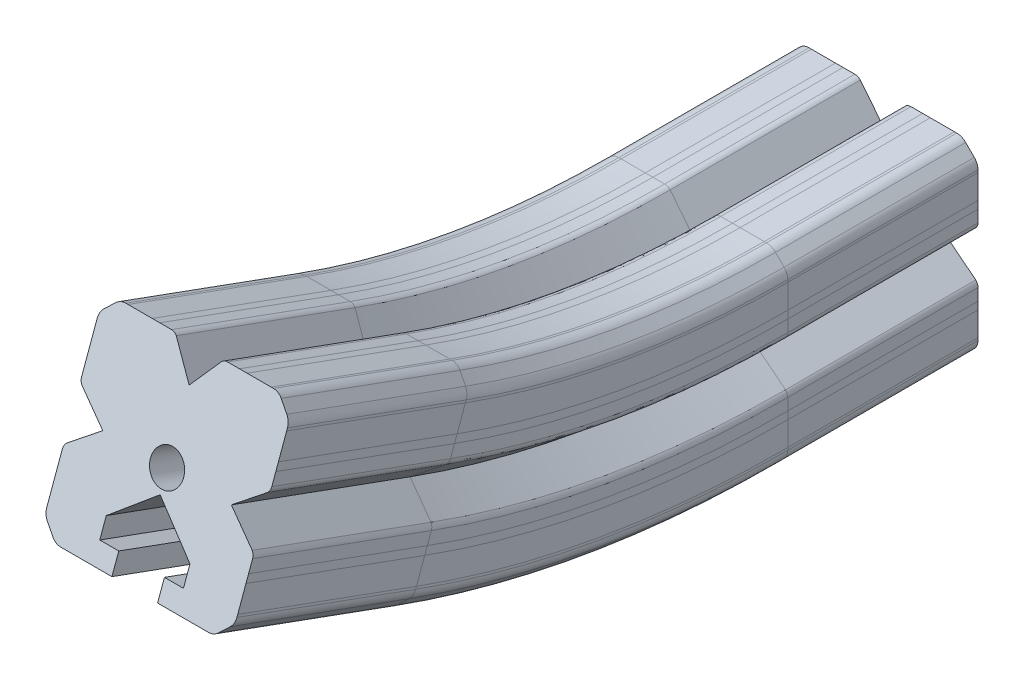
SolidWorks part; units mm, degrees
material "PET"
ref_plane "Front Plane" through (0, 0, 0) normal (0, 0, 1) x (1, 0, 0)
ref_plane "Top Plane" through (0, 0, 0) normal (0, 1, 0) x (1, 0, 0)
ref_plane "Right Plane" through (0, 0, 0) normal (1, 0, 0) x (0, 0, -1)
ref_plane "Plane1" through (0, 0, -304.8) normal (0, 0, -1) x (-1, 0, 0)
sketch "Sketch1" plane through (0, 0, -304.8) normal (0, 0, -1) x (-1, 0, 0)
  line L0 (14.3277, 19.117) -> (9.4982, 19.117)
  line L1 (7.9742, 19.117) -> (5.6176, 19.117)
  line L2 (4.064, 17.5634) -> (4.064, 16.6067) construction
  line L10 (-4.064, 16.6067) -> (-4.064, 17.5634) construction
  line L11 (-5.6176, 19.117) -> (-7.9742, 19.117)
  line L12 (-9.4982, 19.117) -> (-14.3277, 19.117)
  line L13 (-19.05, 14.3948) -> (-19.05, 9.5631)
  line L14 (-19.05, 8.0434) -> (-19.05, 5.6847)
  line L15 (-17.4964, 4.131) -> (-16.5396, 4.131) construction
  line L23 (-16.5396, -3.997) -> (-17.4964, -3.997) construction
  line L24 (-19.05, -5.5506) -> (-19.05, -7.9093)
  line L25 (-19.05, -9.429) -> (-19.05, -14.2607)
  line L26 (-14.3277, -18.983) -> (-9.4961, -18.983)
  line L27 (-7.9763, -18.983) -> (-5.6176, -18.983)
  line L37 (5.6176, -18.983) -> (7.9763, -18.983)
  line L38 (9.4961, -18.983) -> (14.3277, -18.983)
  line L39 (19.05, -14.2607) -> (19.05, -9.429)
  line L40 (19.05, -7.9093) -> (19.05, -5.5506)
  line L41 (17.4964, -3.997) -> (16.5396, -3.997) construction
  line L49 (16.5396, 4.131) -> (17.4964, 4.131) construction
  line L50 (19.05, 5.6847) -> (19.05, 8.0434)
  line L51 (19.05, 9.5631) -> (19.05, 14.3948)
  line L52 (19.05, 5.6847) -> (17.4964, 5.6847) construction
  line L53 (17.4964, 5.6847) -> (17.4964, 4.131) construction
  line L54 (17.4964, 5.6847) -> (18.5065, 4.5043) construction
  line L55 (16.5396, 4.131) -> (12.8784, 0.067) construction
  line L56 (4.064, 16.6067) -> (4.064, 12.9818) construction
  line L57 (4.064, 12.9818) -> (-4.064, 12.9818) construction
  line L58 (-4.064, 12.9818) -> (-4.064, 16.6067) construction
  line L62 (-5.6176, -18.983) -> (5.6176, -18.983)
  line L66 (12.8784, 0.067) -> (16.5396, -3.997) construction
  line L67 (-16.5396, 4.131) -> (-12.8784, 0.067) construction
  line L68 (-12.8784, 0.067) -> (-16.5396, -3.997) construction
  line L69 (-15.8475, 19.117) -> (-14.3277, 19.117)
  line L70 (-9.4982, 19.117) -> (-7.9742, 19.117)
  line L71 (7.9742, 19.117) -> (9.4982, 19.117)
  line L72 (14.3277, 19.117) -> (15.8475, 19.117)
  line L73 (19.05, 15.9145) -> (19.05, 14.3948)
  line L74 (19.05, 9.5631) -> (19.05, 8.0434)
  line L75 (19.05, -7.9093) -> (19.05, -9.429)
  line L76 (19.05, -14.2607) -> (19.05, -15.7805)
  line L77 (15.8475, -18.983) -> (14.3277, -18.983)
  line L78 (9.4961, -18.983) -> (7.9763, -18.983)
  line L79 (-7.9763, -18.983) -> (-9.4961, -18.983)
  line L80 (-14.3277, -18.983) -> (-15.8475, -18.983)
  line L81 (-19.05, -15.7805) -> (-19.05, -14.2607)
  line L82 (-19.05, -9.429) -> (-19.05, -7.9093)
  line L83 (-19.05, 8.0434) -> (-19.05, 9.5631)
  line L84 (-19.05, 14.3948) -> (-19.05, 15.9145)
  line L85 (-15.8475, -18.983) -> (-19.05, -15.7805)
  line L86 (15.8475, -18.983) -> (19.05, -15.7805)
  line L87 (0, 12.9818) -> (4.519, 18.662)
  line L88 (-4.519, 18.662) -> (0, 12.9818)
  line L89 (18.5065, 4.5043) -> (12.8784, 0.067)
  line L90 (12.8784, 0.067) -> (18.595, -4.452)
  line L91 (-18.595, 4.5861) -> (-12.8784, 0.067)
  line L92 (-18.595, -4.452) -> (-12.8784, 0.067)
  line L93 (-19.05, 15.9145) -> (-15.8475, 19.117)
  line L94 (15.8475, 19.117) -> (19.05, 15.9145)
  arc A2 (5.6176, 19.117) -> (4.064, 17.5634) centre (5.6176, 17.5634) ccw construction
  arc A11 (-4.064, 17.5634) -> (-5.6176, 19.117) centre (-5.6176, 17.5634) ccw construction
  arc A14 (-15.8475, 19.117) -> (-19.05, 15.9145) centre (-15.8751, 15.9422) ccw construction
  arc A17 (-19.05, 5.6847) -> (-17.4964, 4.131) centre (-17.4964, 5.6847) ccw construction
  arc A26 (-17.4964, -3.997) -> (-19.05, -5.5506) centre (-17.4964, -5.5506) ccw construction
  arc A29 (-19.05, -15.7805) -> (-15.8475, -18.983) centre (-15.8751, -15.8081) ccw construction
  arc A44 (15.8475, -18.983) -> (19.05, -15.7805) centre (15.8751, -15.8081) ccw construction
  arc A47 (19.05, -5.5506) -> (17.4964, -3.997) centre (17.4964, -5.5506) ccw construction
  arc A56 (17.4964, 4.131) -> (19.05, 5.6847) centre (17.4964, 5.6847) ccw construction
  arc A59 (19.05, 15.9145) -> (15.8475, 19.117) centre (15.8751, 15.9422) ccw construction
  circle A60 centre (0, 0) radius 3.3274 construction
  spline S0 degree 2 poles (-18.595, 4.5861) (-19.0376, 5.0374) (-19.05, 5.6847) knots 0 0 0 1 1 1
  spline S1 degree 2 poles (4.519, 18.662) (4.9741, 19.1064) (5.6176, 19.117) knots 0 0 0 1 1 1
  spline S2 degree 2 poles (-4.519, 18.662) (-4.9741, 19.1064) (-5.6176, 19.117) knots 0 0 0 1 1 1
  spline S3 degree 2 poles (18.5065, 4.5043) (19.0351, 4.9715) (19.05, 5.6847) knots 0 0 0 1 1 1
  spline S4 degree 2 poles (18.595, -4.452) (19.0328, -4.8947) (19.05, -5.5506) knots 0 0 0 1 1 1
  spline S5 degree 2 poles (-18.595, -4.452) (-19.0413, -4.9116) (-19.05, -5.5506) knots 0 0 0 1 1 1
sketch "Sketch2" plane through (0, 0, 0) normal (1, 0, 0) x (0, -1, 0)
  line L1 (0, 266.7) -> (0, 304.8)
  line L2 (-12.2545, 197.2015) -> (-25.2854, 161.3992)
  arc A1 (0, 266.7) -> (-12.2545, 197.2015) centre (-203.2, 266.7) cw
sweep "Sweep4" add profiles "Sketch1" path "Sketch2"
sketch "Sketch10" plane through (0, 0, -304.8) normal (0, 0, -1) x (-1, 0, 0)
  line L1 (4.572, -18.983) -> (4.572, -14.9698)
  line L11 (-5.6176, -18.983) -> (5.6176, -18.983) construction
  line L12 (4.572, -18.983) -> (-4.572, -18.983)
  line L13 (-4.572, -18.983) -> (-4.572, -14.9698)
  line L14 (4.572, -14.9698) -> (8.382, -14.9698)
  line L15 (-4.572, -14.9698) -> (-8.382, -14.9698)
  line L16 (8.382, -14.9698) -> (8.382, -11.1598)
  line L17 (-8.382, -14.9698) -> (-8.382, -11.1598)
  line L18 (-8.382, -11.1598) -> (0, -4.1264)
  line L19 (0, -4.1264) -> (8.382, -11.1598)
  dimension "D1" = 9.144
  dimension "D2" = 4.0132
  dimension "D3" = 3.81
  dimension "D4" = 4.0132
  dimension "D5" = 3.81
  dimension "D6" = 3.81
  dimension "D7" = 3.81
  dimension "D8" = 50
  dimension "D9" = 50
sketch "Sketch12" plane through (0, 0, -304.8) normal (0, 0, -1) x (-1, 0, 0)
  line L0 (-12.8784, 0.067) -> (12.8784, 0.067) construction
  circle A0 centre (0, 0.067) radius 3.3274
extrude "Cut-Extrude3" cut sketch "Sketch12" against normal blind 16.51
sketch "Sketch16" plane through (0, -48.9149, -134.3925) normal (0, 0.342, 0.9397) x (1, 0, 0)
  line L0 (-12.8784, 79.0294) -> (12.8784, 79.0294) construction
  line L1 (5.6176, 59.9793) -> (-5.6176, 59.9793) construction
  line L2 (0, 59.9793) -> (4.065, 59.9793) construction
  line L3 (0, 59.9793) -> (-4.065, 59.9793) construction
  circle A0 centre (0, 79.0294) radius 3.3274
extrude "Cut-Extrude5" cut sketch "Sketch16" against normal blind 16.51
extrude "Cut-Extrude6" cut sketch "Sketch10" against normal blind 38.1
sketch "Sketch17" plane through (0, -48.9149, -134.3925) normal (0, 0.342, 0.9397) x (1, 0, 0)
  line L0 (0, 59.9793) -> (4.6108, 59.9793) construction
  line L1 (5.6176, 59.9793) -> (-5.6176, 59.9793) construction
  line L2 (4.6108, 59.9793) -> (-4.5332, 59.9793)
  line L3 (-4.5332, 59.9793) -> (-4.5332, 63.9925)
  line L4 (-4.5332, 63.9925) -> (-8.3432, 63.9925)
  line L5 (-8.3432, 63.9925) -> (-8.3432, 67.8025)
  line L6 (-8.3432, 67.8025) -> (0.0388, 74.8359)
  line L7 (4.6108, 59.9793) -> (4.6108, 63.9925)
  line L8 (4.6108, 63.9925) -> (8.4208, 63.9925)
  line L9 (8.4208, 63.9925) -> (8.4208, 67.8025)
  line L10 (8.4208, 67.8025) -> (0.0388, 74.8359)
  dimension "D1" = 9.144
  dimension "D2" = 4.0132
  dimension "D3" = 4.0132
  dimension "D4" = 3.81
  dimension "D5" = 3.81
  dimension "D6" = 3.81
  dimension "D7" = 3.81
  dimension "D8" = 50
  dimension "D9" = 50
extrude "Cut-Extrude7" cut sketch "Sketch17" against normal blind 38.1
fillet "Fillet1" radius 2.54 24 edges at (-15.8475, 36.7341, -185.8388) (-15.8475, 21.9137, -234.7343) (-19.05, 33.7247, -184.7435) (-19.05, 18.7598, -234.1782) (-19.05, 3.9411, -173.9031) (-19.05, -12.4537, -228.6744) (-15.8475, 0.9318, -172.8078) (-15.8475, -15.6075, -228.1183) (15.8475, 0.9318, -172.8078) (15.8475, -15.6075, -228.1183) (19.05, 3.9411, -173.9031) (19.05, -12.4537, -228.6744) (19.05, 33.7247, -184.7435) (19.05, 18.7598, -234.1782) (15.8475, 36.7341, -185.8388) (15.8475, 21.9137, -234.7343) (-15.8475, 19.117, -285.75) (-19.05, 15.9145, -285.75) (-19.05, -15.7805, -285.75) (-15.8475, -18.983, -285.75) (15.8475, -18.983, -285.75) (19.05, -15.7805, -285.75) (19.05, 15.9145, -285.75) (15.8475, 19.117, -285.75)
